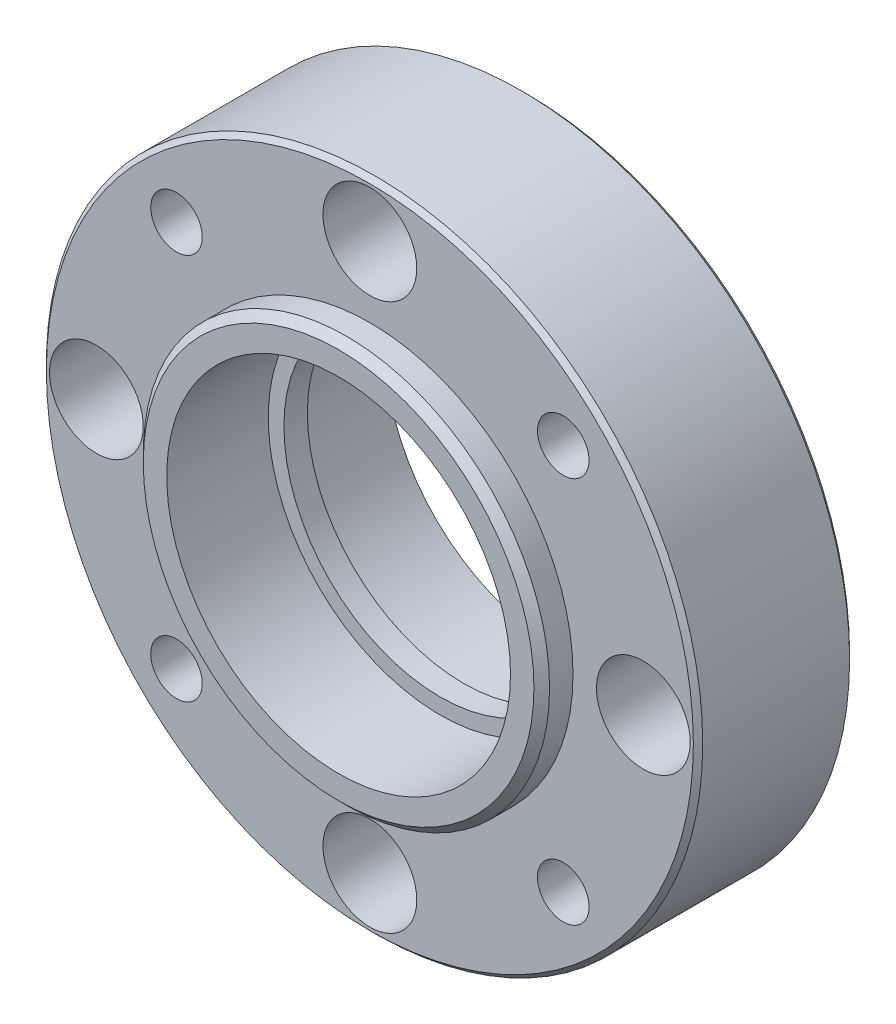
SolidWorks part; units mm, degrees
material "6061 合金"
ref_plane "前视基准面" through (0, 0, 0) normal (0, 0, 1) x (1, 0, 0)
ref_plane "上视基准面" through (0, 0, 0) normal (0, 1, 0) x (1, 0, 0)
ref_plane "右视基准面" through (0, 0, 0) normal (1, 0, 0) x (0, 0, -1)
sketch "草图1" plane through (0, 0, 0) normal (0, 1, 0) x (1, 0, 0)
  line L0 (21, 5) -> (0, 5)
  line L1 (0, 5) -> (0, -5)
  line L2 (0, -5) -> (21, -5)
  line L3 (21, -5) -> (21, 5)
  line L4 (0, 5) -> (0, -5) construction
revolve "旋转1" add sketch "草图1" angle 360 about L4
sketch "草图2" plane through (0, 0, -5) normal (0, 0, -1) x (-1, 0, 0)
  circle A0 centre (0, 0) radius 13.4
extrude "凸台-拉伸1" add sketch "草图2" along normal blind 2
sketch "草图3" plane through (0, 0, 5) normal (0, 0, 1) x (1, 0, 0)
  circle A0 centre (0, 0) radius 13
extrude "凸台-拉伸2" add sketch "草图3" along normal blind 2
sketch "草图4" plane through (0, 0, 0) normal (0, 1, 0) x (1, 0, 0)
  line L0 (11, 7) -> (0, 7)
  line L1 (0, 7) -> (0, -7)
  line L2 (0, -7) -> (11, -7)
  line L3 (11, -7) -> (11, -0.5)
  line L4 (11, -0.5) -> (10, -0.5)
  line L5 (10, -0.5) -> (10, 1)
  line L6 (10, 1) -> (11, 1)
  line L7 (11, 1) -> (11, 7)
  line L8 (0, 7) -> (0, -7) construction
revolve "切除-旋转1" cut sketch "草图4" angle 360 about L8
hole_wizard "M3 六角头机械螺钉的柱形沉头孔1" positions "草图6" profile "草图5" counterbore size "M3" standard "ANSI Metric"
sketch "草图6" plane through (0, 0, 5) normal (0, 0, 1) x (1, 0, 0)
  point P0 (0, 17.5)
  point P1 (17.5, 0)
  point P2 (0, -17.5)
  point P3 (-17.5, 0)
sketch "草图5" plane through (0, 17.5, 5) normal (1, 0, 0) x (0, -1, 0)
  line L0 (0, 0) -> (0, 12)
  line L1 (0, 12) -> (1.75, 12)
  line L3 (1.75, 12) -> (1.75, 5)
  line L4 (1.75, 5) -> (3, 5)
  line L5 (3, 5) -> (3, 0)
  line L7 (3, 0) -> (0, 0)
  line L11 (0, -6.35) -> (0, 107.95) construction
  dimension "通孔孔直径" = 3.5
  dimension "通孔孔深度" = 12
  dimension "柱形沉头孔直径" = 6
  dimension "柱形沉头孔深度" = 5
hole_wizard "Ø3.3 (3.3) 直径孔1" positions "草图8" profile "草图7" hole size "Ø3.3" standard "ANSI Metric"
sketch "草图8" plane through (0, 0, -5) normal (0, 0, -1) x (-1, 0, 0)
  point P0 (12.3744, 12.3744)
  point P1 (-12.3744, 12.3744)
  point P2 (-12.3744, -12.3744)
  point P3 (12.3744, -12.3744)
sketch "草图7" plane through (-12.3744, 12.3744, -5) normal (1, 0, 0) x (0, 1, 0)
  line L0 (0, 0) -> (0, 12)
  line L1 (0, 12) -> (1.65, 12)
  line L2 (1.65, 12) -> (1.65, 0)
  line L5 (1.65, 0) -> (0, 0)
  line L11 (0, -6.35) -> (0, 107.95) construction
  dimension "通孔孔直径" = 3.3
  dimension "通孔孔深度" = 12
chamfer "倒角1" distance 0.3 angle 45 2 edges at (21, 0, -5) (21, 0, 5)
chamfer "倒角2" distance 0.5 angle 45 2 edges at (13, 0, 7) (-13.4, 0, -7)
